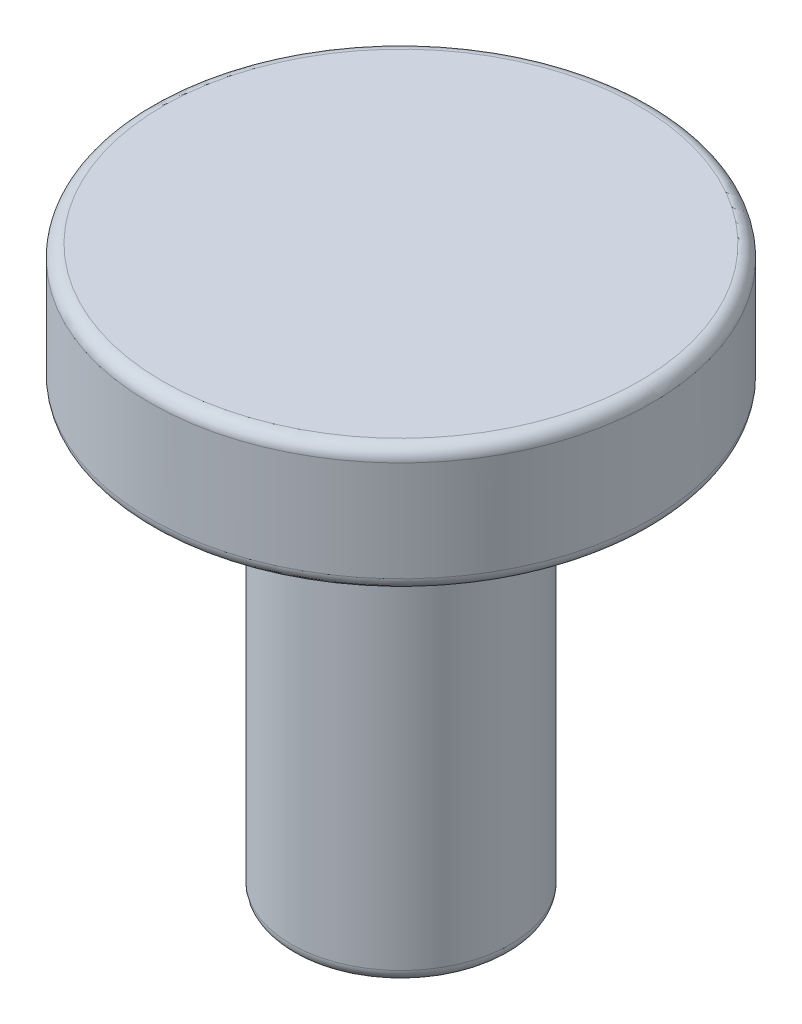
SolidWorks part; units mm, degrees
ref_plane "Front Plane" through (0, 0, 0) normal (0, 0, 1) x (1, 0, 0)
ref_plane "Top Plane" through (0, 0, 0) normal (0, 1, 0) x (1, 0, 0)
ref_plane "Right Plane" through (0, 0, 0) normal (1, 0, 0) x (0, 0, -1)
sketch "Sketch1" plane through (0, 0, 0) normal (1, 0, 0) x (0, 0, -1)
  line L0 (0, 0) -> (-1.75, 0)
  line L1 (-1.75, 0) -> (-1.75, 9)
  line L2 (-1.75, 9) -> (2.25, 9)
  line L3 (2.25, 9) -> (2.25, 7)
  line L4 (2.25, 7) -> (0, 7)
  line L5 (0, 7) -> (0, 0)
  dimension "D1" = 1.75
  dimension "D2" = 4
  dimension "D3" = 7
  dimension "D4" = 9
revolve "Revolve1" add sketch "Sketch1" angle 360 about L1
fillet "Fillet1" radius 0.2 3 edges at (0, 0, 0) (0, 9, -2.25) (0, 7, -2.25)
